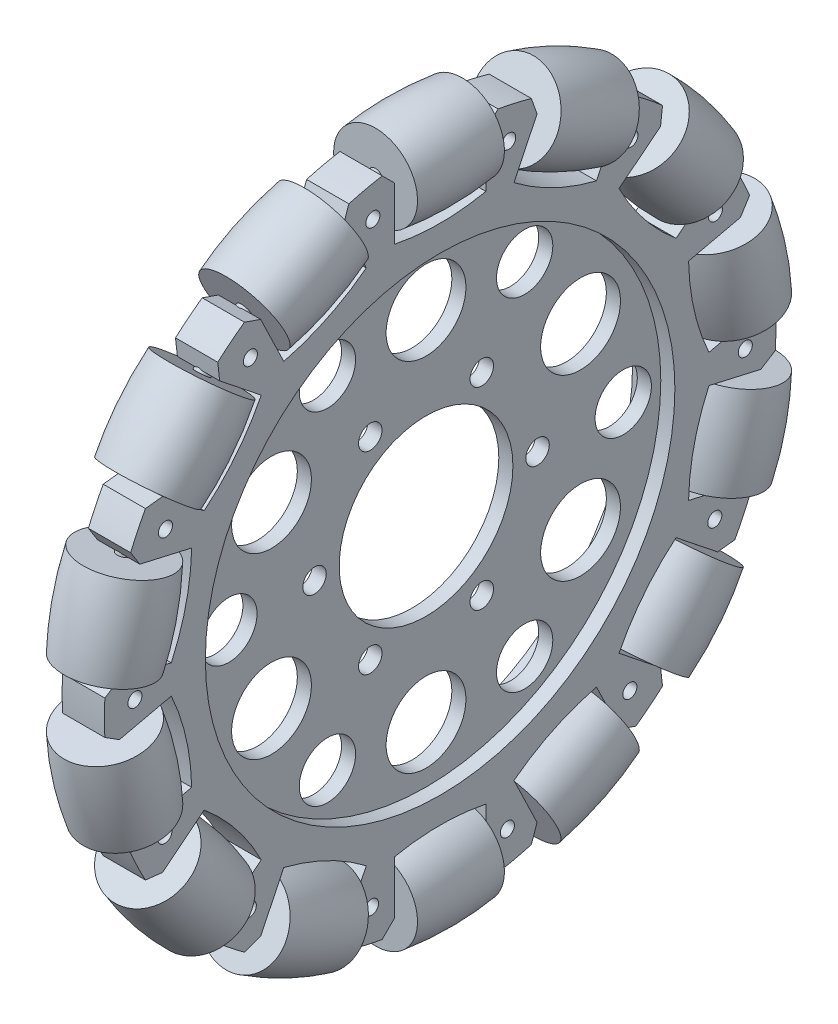
SolidWorks part; units mm, degrees
ref_plane "Front Plane" through (0, 0, 0) normal (0, 0, 1) x (1, 0, 0)
ref_plane "Top Plane" through (0, 0, 0) normal (0, 1, 0) x (1, 0, 0)
ref_plane "Right Plane" through (0, 0, 0) normal (1, 0, 0) x (0, 0, -1)
sketch "Sketch1" plane through (0, 0, 0) normal (1, 0, 0) x (0, 0, -1)
  line L0 (-23.75, 0) -> (0, 0) construction
  line L1 (-42, 0) -> (-23.75, 0) construction
  line L2 (-32.909, 19) -> (0, 0) construction
  line L3 (-9.25, 57.565) -> (-9.25, 75.435) construction
  line L4 (0, 0) -> (0, 66.5) construction
  line L5 (9.25, 66.5) -> (-9.25, 66.5) construction
  line L6 (9.25, 57.565) -> (9.25, 75.435) construction
  line L7 (-9.75, 67.8321) -> (-9.75, 56.5)
  line L8 (9.75, 67.8321) -> (9.75, 56.5)
  line L9 (20.6468, 65.345) -> (15.73, 55.1351)
  line L10 (38.2157, 56.8843) -> (33.2989, 46.6744)
  line L11 (46.9543, 49.9155) -> (38.0945, 42.85)
  line L12 (59.1123, 34.6698) -> (50.2525, 27.6043)
  line L13 (63.9618, 24.5996) -> (52.9138, 22.078)
  line L14 (68.301, 5.5885) -> (57.253, 3.0669)
  line L15 (68.301, -5.5885) -> (57.253, -3.0669)
  line L16 (63.9618, -24.5996) -> (52.9138, -22.078)
  line L17 (59.1123, -34.6698) -> (50.2525, -27.6043)
  line L18 (46.9543, -49.9155) -> (38.0945, -42.85)
  line L19 (38.2157, -56.8843) -> (33.2989, -46.6744)
  line L20 (20.6468, -65.345) -> (15.73, -55.1351)
  line L21 (9.75, -67.8321) -> (9.75, -56.5)
  line L22 (-9.75, -67.8321) -> (-9.75, -56.5)
  line L23 (-20.6468, -65.345) -> (-15.73, -55.1351)
  line L24 (-38.2157, -56.8843) -> (-33.2989, -46.6744)
  line L25 (-46.9543, -49.9155) -> (-38.0945, -42.85)
  line L26 (-59.1123, -34.6698) -> (-50.2525, -27.6043)
  line L27 (-63.9618, -24.5996) -> (-52.9138, -22.078)
  line L28 (-68.301, -5.5885) -> (-57.253, -3.0669)
  line L29 (-68.301, 5.5885) -> (-57.253, 3.0669)
  line L30 (-63.9618, 24.5996) -> (-52.9138, 22.078)
  line L31 (-59.1123, 34.6698) -> (-50.2525, 27.6043)
  line L32 (-46.9543, 49.9155) -> (-38.0945, 42.85)
  line L33 (-38.2157, 56.8843) -> (-33.2989, 46.6744)
  line L34 (-20.6468, 65.345) -> (-15.73, 55.1351)
  line L35 (0, 0) -> (-14.3209, 63.4028) construction
  line L36 (-9.75, 67.8321) -> (-12.3442, 70.4263)
  line L37 (9.75, 67.8321) -> (12.3442, 70.4263)
  line L38 (20.6468, 65.345) -> (19.4351, 68.8079)
  line L39 (38.2157, 56.8843) -> (41.6786, 58.096)
  line L40 (46.9543, 49.9155) -> (47.365, 53.5612)
  line L41 (59.1123, 34.6698) -> (62.758, 34.259)
  line L42 (63.9618, 24.5996) -> (65.9138, 27.7061)
  line L43 (68.301, 5.5885) -> (71.4075, 3.6366)
  line L44 (68.301, -5.5885) -> (71.4075, -3.6366)
  line L45 (63.9618, -24.5996) -> (65.9138, -27.7061)
  line L46 (59.1123, -34.6698) -> (62.758, -34.259)
  line L47 (46.9543, -49.9155) -> (47.365, -53.5612)
  line L48 (38.2157, -56.8843) -> (41.6786, -58.096)
  line L49 (20.6468, -65.345) -> (19.4351, -68.8079)
  line L50 (9.75, -67.8321) -> (12.3442, -70.4263)
  line L51 (-9.75, -67.8321) -> (-12.3442, -70.4263)
  line L52 (-20.6468, -65.345) -> (-19.4351, -68.8079)
  line L53 (-38.2157, -56.8843) -> (-41.6786, -58.096)
  line L54 (-46.9543, -49.9155) -> (-47.365, -53.5612)
  line L55 (-59.1123, -34.6698) -> (-62.758, -34.259)
  line L56 (-63.9618, -24.5996) -> (-65.9138, -27.7061)
  line L57 (-68.301, -5.5885) -> (-71.4075, -3.6366)
  line L58 (-68.301, 5.5885) -> (-71.4075, 3.6366)
  line L59 (-63.9618, 24.5996) -> (-65.9138, 27.7061)
  line L60 (-59.1123, 34.6698) -> (-62.758, 34.259)
  line L61 (-46.9543, 49.9155) -> (-47.365, 53.5612)
  line L62 (-38.2157, 56.8843) -> (-41.6786, 58.096)
  line L63 (-20.6468, 65.345) -> (-19.4351, 68.8079)
  arc A0 (-12.3442, 70.4263) -> (-19.4351, 68.8079) centre (0, 0) ccw
  circle A1 centre (0, 0) radius 18.5
  circle A2 centre (-23.75, 0) radius 2.5
  circle A3 centre (-42, 0) radius 6
  circle A4 centre (-32.909, 19) radius 8.5
  circle A5 centre (0, 38) radius 8.5
  circle A6 centre (-21, 36.3731) radius 6
  circle A7 centre (-11.875, 20.5681) radius 2.5
  circle A8 centre (32.909, 19) radius 8.5
  circle A9 centre (21, 36.3731) radius 6
  circle A10 centre (11.875, 20.5681) radius 2.5
  circle A11 centre (32.909, -19) radius 8.5
  circle A12 centre (42, 0) radius 6
  circle A13 centre (23.75, 0) radius 2.5
  circle A14 centre (0, -38) radius 8.5
  circle A15 centre (21, -36.3731) radius 6
  circle A16 centre (11.875, -20.5681) radius 2.5
  circle A17 centre (-32.909, -19) radius 8.5
  circle A18 centre (-21, -36.3731) radius 6
  circle A19 centre (-11.875, -20.5681) radius 2.5
  arc A20 (9.25, 75.435) -> (-9.25, 75.435) centre (0, 0) ccw construction
  arc A21 (9.25, 57.565) -> (-9.25, 57.565) centre (0, 133) cw construction
  arc A22 (-9.75, 56.5) -> (9.75, 56.5) centre (0, 103.5312) ccw
  arc A23 (15.73, 55.1351) -> (33.2989, 46.6744) centre (44.9205, 93.2784) ccw
  arc A24 (38.0945, 42.85) -> (50.2525, 27.6043) centre (80.944, 64.5507) ccw
  arc A25 (52.9138, 22.078) -> (57.253, 3.0669) centre (100.9355, 23.0379) ccw
  arc A26 (57.253, -3.0669) -> (52.9138, -22.078) centre (100.9355, -23.0379) ccw
  arc A27 (50.2525, -27.6043) -> (38.0945, -42.85) centre (80.944, -64.5507) ccw
  arc A28 (33.2989, -46.6744) -> (15.73, -55.1351) centre (44.9205, -93.2784) ccw
  arc A29 (9.75, -56.5) -> (-9.75, -56.5) centre (0, -103.5312) ccw
  arc A30 (-15.73, -55.1351) -> (-33.2989, -46.6744) centre (-44.9205, -93.2784) ccw
  arc A31 (-38.0945, -42.85) -> (-50.2525, -27.6043) centre (-80.944, -64.5507) ccw
  arc A32 (-52.9138, -22.078) -> (-57.253, -3.0669) centre (-100.9355, -23.0379) ccw
  arc A33 (-57.253, 3.0669) -> (-52.9138, 22.078) centre (-100.9355, 23.0379) ccw
  arc A34 (-50.2525, 27.6043) -> (-38.0945, 42.85) centre (-80.944, 64.5507) ccw
  arc A35 (-33.2989, 46.6744) -> (-15.73, 55.1351) centre (-44.9205, 93.2784) ccw
  arc A36 (-41.6786, 58.096) -> (-47.365, 53.5612) centre (0, 0) ccw
  arc A37 (19.4351, 68.8079) -> (12.3442, 70.4263) centre (0, 0) ccw
  arc A38 (-62.758, 34.259) -> (-65.9138, 27.7061) centre (0, 0) ccw
  arc A39 (-71.4075, 3.6366) -> (-71.4075, -3.6366) centre (0, 0) ccw
  arc A40 (-65.9138, -27.7061) -> (-62.758, -34.259) centre (0, 0) ccw
  arc A41 (-47.365, -53.5612) -> (-41.6786, -58.096) centre (0, 0) ccw
  arc A42 (-19.4351, -68.8079) -> (-12.3442, -70.4263) centre (0, 0) ccw
  arc A43 (12.3442, -70.4263) -> (19.4351, -68.8079) centre (0, 0) ccw
  arc A44 (41.6786, -58.096) -> (47.365, -53.5612) centre (0, 0) ccw
  arc A45 (62.758, -34.259) -> (65.9138, -27.7061) centre (0, 0) ccw
  arc A46 (71.4075, -3.6366) -> (71.4075, 3.6366) centre (0, 0) ccw
  arc A47 (65.9138, 27.7061) -> (62.758, 34.259) centre (0, 0) ccw
  arc A48 (47.365, 53.5612) -> (41.6786, 58.096) centre (0, 0) ccw
  circle A49 centre (-14.3209, 63.4028) radius 1.5
  circle A50 centre (14.6068, 63.3375) radius 1.5
  circle A51 centre (40.6414, 50.7275) radius 1.5
  circle A52 centre (58.6264, 28.0703) radius 1.5
  circle A53 centre (64.9998, -0.1466) radius 1.5
  circle A54 centre (58.4992, -28.3345) radius 1.5
  circle A55 centre (40.4121, -50.9103) radius 1.5
  circle A56 centre (14.3209, -63.4028) radius 1.5
  circle A57 centre (-14.6068, -63.3375) radius 1.5
  circle A58 centre (-40.6414, -50.7275) radius 1.5
  circle A59 centre (-58.6264, -28.0703) radius 1.5
  circle A60 centre (-64.9998, 0.1466) radius 1.5
  circle A61 centre (-58.4992, 28.3345) radius 1.5
  circle A62 centre (-40.4121, 50.9103) radius 1.5
  point P42 (0, 0)
  point P45 (0, 76)
  point P46 (0, 57)
  point P47 (0, 66.5)
  point P51 (0, 66.5)
  point P55 (0, 55.5)
  point P125 (0, 0)
  point P154 (0, 0)
  point P209 (0, 0)
  dimension "D1" = 143
  dimension "D2" = 37
  dimension "D3" = 5
  dimension "D4" = 12
  dimension "D5" = 17
  dimension "D11" = 152
  dimension "D19" = 3
  dimension "D6" = 30
  dimension "D7" = 23.75
  dimension "D8" = 42
  dimension "D9" = 38
  dimension "D12" = 19
  dimension "D13" = 9.25
  dimension "D14" = 9.5
  dimension "D15" = 0.5
  dimension "D16" = 1
  dimension "D17" = 1.5
  dimension "D20" = 65
  dimension "D22" = 14
  dimension "D10" = 6
  dimension "D18" = 14
  dimension "D21" = 14
extrude "Boss-Extrude1" add sketch "Sketch1" along normal blind 3
sketch "Sketch2" plane through (3, 0, 0) normal (1, 0, 0) x (0, 0, -1)
  line L28 (9.75, 67.8321) -> (9.75, 56.5)
  line L29 (-9.75, 56.5) -> (-9.75, 67.8321)
  line L30 (-20.6468, 65.345) -> (-15.73, 55.1351)
  line L31 (-33.2989, 46.6744) -> (-38.2157, 56.8843)
  line L32 (-46.9543, 49.9155) -> (-38.0945, 42.85)
  line L33 (-50.2525, 27.6043) -> (-59.1123, 34.6698)
  line L34 (-63.9618, 24.5996) -> (-52.9138, 22.078)
  line L35 (-57.253, 3.0669) -> (-68.301, 5.5885)
  line L36 (-68.301, -5.5885) -> (-57.253, -3.0669)
  line L37 (-52.9138, -22.078) -> (-63.9618, -24.5996)
  line L38 (-59.1123, -34.6698) -> (-50.2525, -27.6043)
  line L39 (-38.0945, -42.85) -> (-46.9543, -49.9155)
  line L40 (-38.2157, -56.8843) -> (-33.2989, -46.6744)
  line L41 (-15.73, -55.1351) -> (-20.6468, -65.345)
  line L42 (-9.75, -67.8321) -> (-9.75, -56.5)
  line L43 (9.75, -56.5) -> (9.75, -67.8321)
  line L44 (20.6468, -65.345) -> (15.73, -55.1351)
  line L45 (33.2989, -46.6744) -> (38.2157, -56.8843)
  line L46 (46.9543, -49.9155) -> (38.0945, -42.85)
  line L47 (50.2525, -27.6043) -> (59.1123, -34.6698)
  line L48 (63.9618, -24.5996) -> (52.9138, -22.078)
  line L49 (57.253, -3.0669) -> (68.301, -5.5885)
  line L50 (68.301, 5.5885) -> (57.253, 3.0669)
  line L51 (52.9138, 22.078) -> (63.9618, 24.5996)
  line L52 (59.1123, 34.6698) -> (50.2525, 27.6043)
  line L53 (38.0945, 42.85) -> (46.9543, 49.9155)
  line L54 (38.2157, 56.8843) -> (33.2989, 46.6744)
  line L55 (15.73, 55.1351) -> (20.6468, 65.345)
  line L56 (9.75, 67.8321) -> (9.75, 56.5)
  line L57 (-9.75, 56.5) -> (-9.75, 67.8321)
  line L58 (-20.6468, 65.345) -> (-15.73, 55.1351)
  line L59 (-33.2989, 46.6744) -> (-38.2157, 56.8843)
  line L60 (-46.9543, 49.9155) -> (-38.0945, 42.85)
  line L61 (-50.2525, 27.6043) -> (-59.1123, 34.6698)
  line L62 (-63.9618, 24.5996) -> (-52.9138, 22.078)
  line L63 (-57.253, 3.0669) -> (-68.301, 5.5885)
  line L64 (-68.301, -5.5885) -> (-57.253, -3.0669)
  line L65 (-52.9138, -22.078) -> (-63.9618, -24.5996)
  line L66 (-59.1123, -34.6698) -> (-50.2525, -27.6043)
  line L67 (-38.0945, -42.85) -> (-46.9543, -49.9155)
  line L68 (-38.2157, -56.8843) -> (-33.2989, -46.6744)
  line L69 (-15.73, -55.1351) -> (-20.6468, -65.345)
  line L70 (-9.75, -67.8321) -> (-9.75, -56.5)
  line L71 (9.75, -56.5) -> (9.75, -67.8321)
  line L72 (20.6468, -65.345) -> (15.73, -55.1351)
  line L73 (33.2989, -46.6744) -> (38.2157, -56.8843)
  line L74 (46.9543, -49.9155) -> (38.0945, -42.85)
  line L75 (50.2525, -27.6043) -> (59.1123, -34.6698)
  line L76 (63.9618, -24.5996) -> (52.9138, -22.078)
  line L77 (57.253, -3.0669) -> (68.301, -5.5885)
  line L78 (68.301, 5.5885) -> (57.253, 3.0669)
  line L79 (52.9138, 22.078) -> (63.9618, 24.5996)
  line L80 (59.1123, 34.6698) -> (50.2525, 27.6043)
  line L81 (38.0945, 42.85) -> (46.9543, 49.9155)
  line L82 (38.2157, 56.8843) -> (33.2989, 46.6744)
  line L83 (15.73, 55.1351) -> (20.6468, 65.345)
  line L112 (12.3442, 70.4263) -> (9.75, 67.8321)
  line L113 (12.3442, 70.4263) -> (9.75, 67.8321)
  line L114 (-9.75, 67.8321) -> (-12.3442, 70.4263)
  line L115 (-9.75, 67.8321) -> (-12.3442, 70.4263)
  line L116 (-19.4351, 68.8079) -> (-20.6468, 65.345)
  line L117 (-19.4351, 68.8079) -> (-20.6468, 65.345)
  line L118 (-38.2157, 56.8843) -> (-41.6786, 58.096)
  line L119 (-38.2157, 56.8843) -> (-41.6786, 58.096)
  line L120 (-47.365, 53.5612) -> (-46.9543, 49.9155)
  line L121 (-47.365, 53.5612) -> (-46.9543, 49.9155)
  line L122 (-59.1123, 34.6698) -> (-62.758, 34.259)
  line L123 (-59.1123, 34.6698) -> (-62.758, 34.259)
  line L124 (-65.9138, 27.7061) -> (-63.9618, 24.5996)
  line L125 (-65.9138, 27.7061) -> (-63.9618, 24.5996)
  line L126 (-68.301, 5.5885) -> (-71.4075, 3.6366)
  line L127 (-68.301, 5.5885) -> (-71.4075, 3.6366)
  line L128 (-71.4075, -3.6366) -> (-68.301, -5.5885)
  line L129 (-71.4075, -3.6366) -> (-68.301, -5.5885)
  line L130 (-63.9618, -24.5996) -> (-65.9138, -27.7061)
  line L131 (-63.9618, -24.5996) -> (-65.9138, -27.7061)
  line L132 (-62.758, -34.259) -> (-59.1123, -34.6698)
  line L133 (-62.758, -34.259) -> (-59.1123, -34.6698)
  line L134 (-46.9543, -49.9155) -> (-47.365, -53.5612)
  line L135 (-46.9543, -49.9155) -> (-47.365, -53.5612)
  line L136 (-41.6786, -58.096) -> (-38.2157, -56.8843)
  line L137 (-41.6786, -58.096) -> (-38.2157, -56.8843)
  line L138 (-20.6468, -65.345) -> (-19.4351, -68.8079)
  line L139 (-20.6468, -65.345) -> (-19.4351, -68.8079)
  line L140 (-12.3442, -70.4263) -> (-9.75, -67.8321)
  line L141 (-12.3442, -70.4263) -> (-9.75, -67.8321)
  line L142 (9.75, -67.8321) -> (12.3442, -70.4263)
  line L143 (9.75, -67.8321) -> (12.3442, -70.4263)
  line L144 (19.4351, -68.8079) -> (20.6468, -65.345)
  line L145 (19.4351, -68.8079) -> (20.6468, -65.345)
  line L146 (38.2157, -56.8843) -> (41.6786, -58.096)
  line L147 (38.2157, -56.8843) -> (41.6786, -58.096)
  line L148 (47.365, -53.5612) -> (46.9543, -49.9155)
  line L149 (47.365, -53.5612) -> (46.9543, -49.9155)
  line L150 (59.1123, -34.6698) -> (62.758, -34.259)
  line L151 (59.1123, -34.6698) -> (62.758, -34.259)
  line L152 (65.9138, -27.7061) -> (63.9618, -24.5996)
  line L153 (65.9138, -27.7061) -> (63.9618, -24.5996)
  line L154 (68.301, -5.5885) -> (71.4075, -3.6366)
  line L155 (68.301, -5.5885) -> (71.4075, -3.6366)
  line L156 (71.4075, 3.6366) -> (68.301, 5.5885)
  line L157 (71.4075, 3.6366) -> (68.301, 5.5885)
  line L158 (63.9618, 24.5996) -> (65.9138, 27.7061)
  line L159 (63.9618, 24.5996) -> (65.9138, 27.7061)
  line L160 (62.758, 34.259) -> (59.1123, 34.6698)
  line L161 (62.758, 34.259) -> (59.1123, 34.6698)
  line L162 (46.9543, 49.9155) -> (47.365, 53.5612)
  line L163 (46.9543, 49.9155) -> (47.365, 53.5612)
  line L164 (41.6786, 58.096) -> (38.2157, 56.8843)
  line L165 (41.6786, 58.096) -> (38.2157, 56.8843)
  line L166 (20.6468, 65.345) -> (19.4351, 68.8079)
  line L167 (20.6468, 65.345) -> (19.4351, 68.8079)
  circle A0 centre (0, 0) radius 50
  circle A1 centre (14.6068, 63.3375) radius 1.5
  circle A2 centre (-14.3209, 63.4028) radius 1.5 construction
  circle A3 centre (-14.3209, 63.4028) radius 1.5
  circle A4 centre (40.6414, 50.7275) radius 1.5
  circle A5 centre (58.6264, 28.0703) radius 1.5
  circle A6 centre (64.9998, -0.1466) radius 1.5
  circle A7 centre (58.4992, -28.3345) radius 1.5
  circle A8 centre (40.4121, -50.9103) radius 1.5
  circle A9 centre (14.3209, -63.4028) radius 1.5
  circle A10 centre (-14.6068, -63.3375) radius 1.5
  circle A11 centre (-40.6414, -50.7275) radius 1.5
  circle A12 centre (-58.6264, -28.0703) radius 1.5
  circle A13 centre (-64.9998, 0.1466) radius 1.5
  circle A14 centre (-58.4992, 28.3345) radius 1.5
  circle A15 centre (-40.4121, 50.9103) radius 1.5
  arc A28 (19.4351, 68.8079) -> (12.3442, 70.4263) centre (0, 0) ccw
  arc A29 (-9.75, 56.5) -> (9.75, 56.5) centre (0, 103.5312) ccw
  arc A30 (-12.3442, 70.4263) -> (-19.4351, 68.8079) centre (0, 0) ccw
  arc A31 (-33.2989, 46.6744) -> (-15.73, 55.1351) centre (-44.9205, 93.2784) ccw
  arc A32 (-41.6786, 58.096) -> (-47.365, 53.5612) centre (0, 0) ccw
  arc A33 (-50.2525, 27.6043) -> (-38.0945, 42.85) centre (-80.944, 64.5507) ccw
  arc A34 (-62.758, 34.259) -> (-65.9138, 27.7061) centre (0, 0) ccw
  arc A35 (-57.253, 3.0669) -> (-52.9138, 22.078) centre (-100.9355, 23.0379) ccw
  arc A36 (-71.4075, 3.6366) -> (-71.4075, -3.6366) centre (0, 0) ccw
  arc A37 (-52.9138, -22.078) -> (-57.253, -3.0669) centre (-100.9355, -23.0379) ccw
  arc A38 (-65.9138, -27.7061) -> (-62.758, -34.259) centre (0, 0) ccw
  arc A39 (-38.0945, -42.85) -> (-50.2525, -27.6043) centre (-80.944, -64.5507) ccw
  arc A40 (-47.365, -53.5612) -> (-41.6786, -58.096) centre (0, 0) ccw
  arc A41 (-15.73, -55.1351) -> (-33.2989, -46.6744) centre (-44.9205, -93.2784) ccw
  arc A42 (-19.4351, -68.8079) -> (-12.3442, -70.4263) centre (0, 0) ccw
  arc A43 (9.75, -56.5) -> (-9.75, -56.5) centre (0, -103.5312) ccw
  arc A44 (12.3442, -70.4263) -> (19.4351, -68.8079) centre (0, 0) ccw
  arc A45 (33.2989, -46.6744) -> (15.73, -55.1351) centre (44.9205, -93.2784) ccw
  arc A46 (41.6786, -58.096) -> (47.365, -53.5612) centre (0, 0) ccw
  arc A47 (50.2525, -27.6043) -> (38.0945, -42.85) centre (80.944, -64.5507) ccw
  arc A48 (62.758, -34.259) -> (65.9138, -27.7061) centre (0, 0) ccw
  arc A49 (57.253, -3.0669) -> (52.9138, -22.078) centre (100.9355, -23.0379) ccw
  arc A50 (71.4075, -3.6366) -> (71.4075, 3.6366) centre (0, 0) ccw
  arc A51 (52.9138, 22.078) -> (57.253, 3.0669) centre (100.9355, 23.0379) ccw
  arc A52 (65.9138, 27.7061) -> (62.758, 34.259) centre (0, 0) ccw
  arc A53 (38.0945, 42.85) -> (50.2525, 27.6043) centre (80.944, 64.5507) ccw
  arc A54 (47.365, 53.5612) -> (41.6786, 58.096) centre (0, 0) ccw
  arc A55 (15.73, 55.1351) -> (33.2989, 46.6744) centre (44.9205, 93.2784) ccw
  arc A56 (19.4351, 68.8079) -> (12.3442, 70.4263) centre (0, 0) ccw
  arc A57 (-9.75, 56.5) -> (9.75, 56.5) centre (0, 103.5312) ccw
  arc A58 (-12.3442, 70.4263) -> (-19.4351, 68.8079) centre (0, 0) ccw
  arc A59 (-33.2989, 46.6744) -> (-15.73, 55.1351) centre (-44.9205, 93.2784) ccw
  arc A60 (-41.6786, 58.096) -> (-47.365, 53.5612) centre (0, 0) ccw
  arc A61 (-50.2525, 27.6043) -> (-38.0945, 42.85) centre (-80.944, 64.5507) ccw
  arc A62 (-62.758, 34.259) -> (-65.9138, 27.7061) centre (0, 0) ccw
  arc A63 (-57.253, 3.0669) -> (-52.9138, 22.078) centre (-100.9355, 23.0379) ccw
  arc A64 (-71.4075, 3.6366) -> (-71.4075, -3.6366) centre (0, 0) ccw
  arc A65 (-52.9138, -22.078) -> (-57.253, -3.0669) centre (-100.9355, -23.0379) ccw
  arc A66 (-65.9138, -27.7061) -> (-62.758, -34.259) centre (0, 0) ccw
  arc A67 (-38.0945, -42.85) -> (-50.2525, -27.6043) centre (-80.944, -64.5507) ccw
  arc A68 (-47.365, -53.5612) -> (-41.6786, -58.096) centre (0, 0) ccw
  arc A69 (-15.73, -55.1351) -> (-33.2989, -46.6744) centre (-44.9205, -93.2784) ccw
  arc A70 (-19.4351, -68.8079) -> (-12.3442, -70.4263) centre (0, 0) ccw
  arc A71 (9.75, -56.5) -> (-9.75, -56.5) centre (0, -103.5312) ccw
  arc A72 (12.3442, -70.4263) -> (19.4351, -68.8079) centre (0, 0) ccw
  arc A73 (33.2989, -46.6744) -> (15.73, -55.1351) centre (44.9205, -93.2784) ccw
  arc A74 (41.6786, -58.096) -> (47.365, -53.5612) centre (0, 0) ccw
  arc A75 (50.2525, -27.6043) -> (38.0945, -42.85) centre (80.944, -64.5507) ccw
  arc A76 (62.758, -34.259) -> (65.9138, -27.7061) centre (0, 0) ccw
  arc A77 (57.253, -3.0669) -> (52.9138, -22.078) centre (100.9355, -23.0379) ccw
  arc A78 (71.4075, -3.6366) -> (71.4075, 3.6366) centre (0, 0) ccw
  arc A79 (52.9138, 22.078) -> (57.253, 3.0669) centre (100.9355, 23.0379) ccw
  arc A80 (65.9138, 27.7061) -> (62.758, 34.259) centre (0, 0) ccw
  arc A81 (38.0945, 42.85) -> (50.2525, 27.6043) centre (80.944, 64.5507) ccw
  arc A82 (47.365, 53.5612) -> (41.6786, 58.096) centre (0, 0) ccw
  arc A83 (15.73, 55.1351) -> (33.2989, 46.6744) centre (44.9205, 93.2784) ccw
  point P101 (0, 0)
  dimension "D2" = 100
  dimension "D1" = 0
  dimension "D3" = 14
extrude "Boss-Extrude2" add sketch "Sketch2" along normal blind 3
pattern_linear "LPattern1" count 2 spacing 6 along (-1, 0, 0) of "Boss-Extrude2"
ref_plane "Plane1" through (1.5, 0, 0) normal (1, 0, 0) x (0, 0, -1)
sketch "Sketch3" plane through (1.5, 0, 0) normal (1, 0, 0) x (0, 0, -1)
  line L0 (-9.25, 75.435) -> (-9.25, 68)
  line L1 (0, 0) -> (0, 76) construction
  line L2 (9.25, 75.435) -> (9.25, 68)
  line L3 (9.25, 66.5) -> (-9.25, 66.5)
  line L4 (-9.75, 56.5) -> (-9.75, 67.8321) construction
  line L5 (-9.25, 66.5) -> (-11.3785, 66.5)
  line L6 (-11.3785, 66.5) -> (-11.3785, 68)
  line L7 (-11.3785, 68) -> (-9.25, 68)
  line L8 (9.25, 66.5) -> (11.3785, 66.5)
  line L9 (11.3785, 66.5) -> (11.3785, 68)
  line L10 (11.3785, 68) -> (9.25, 68)
  arc A0 (9.25, 75.435) -> (-9.25, 75.435) centre (0, 0) ccw
  point P8 (0, 66.5)
  point P12 (0, 66.5)
  dimension "D1" = 152
  dimension "D2" = 9.5
  dimension "D3" = 0.5
  dimension "D4" = 1.5
revolve "Revolve1" add sketch "Sketch3" angle 360 about L3
pattern_circular "CirPattern1" count 14 over 360 about axis through (0, 0, 0) along (1, 0, 0) of "Revolve1"
